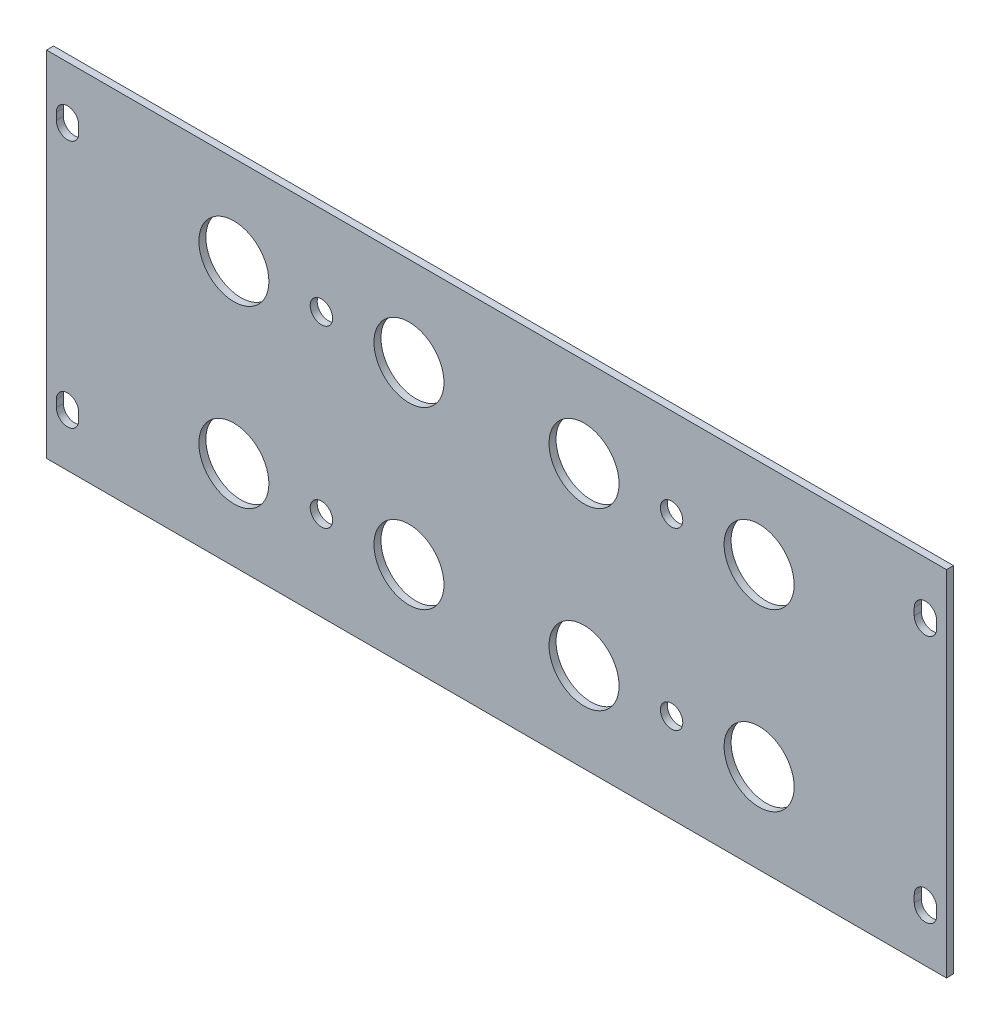
SolidWorks part; units mm, degrees
ref_plane "Plan de face" through (0, 0, 0) normal (0, 0, 1) x (1, 0, 0)
ref_plane "Plan de dessus" through (0, 0, 0) normal (0, 1, 0) x (1, 0, 0)
ref_plane "Plan de droite" through (0, 0, 0) normal (1, 0, 0) x (0, 0, -1)
sketch "Esquisse1" plane through (0, 0, 0) normal (0, 0, 1) x (1, 0, 0)
  line L0 (-64.25, 25.25) -> (-64.25, -25.25)
  line L1 (-64.25, 25.25) -> (-64.25, -25.25)
  line L2 (-64.25, -25.25) -> (64.25, -25.25)
  line L3 (-64.25, -25.25) -> (64.25, -25.25)
  line L4 (64.25, -25.25) -> (64.25, 25.25)
  line L5 (64.25, -25.25) -> (64.25, 25.25)
  line L6 (64.25, 25.25) -> (-64.25, 25.25)
  line L7 (64.25, 25.25) -> (-64.25, 25.25)
  line L8 (-59.65, 17.25) -> (-59.65, 18.25)
  line L9 (-59.65, 17.25) -> (-59.65, 18.25)
  line L10 (-62.85, 18.25) -> (-62.85, 17.25)
  line L11 (-62.85, 18.25) -> (-62.85, 17.25)
  line L12 (-59.65, -18.25) -> (-59.65, -17.25)
  line L13 (-59.65, -18.25) -> (-59.65, -17.25)
  line L14 (-62.85, -17.25) -> (-62.85, -18.25)
  line L15 (-62.85, -17.25) -> (-62.85, -18.25)
  line L16 (59.65, 18.25) -> (59.65, 17.25)
  line L17 (59.65, 18.25) -> (59.65, 17.25)
  line L18 (62.85, 17.25) -> (62.85, 18.25)
  line L19 (62.85, 17.25) -> (62.85, 18.25)
  line L20 (62.85, -18.25) -> (62.85, -17.25)
  line L21 (62.85, -18.25) -> (62.85, -17.25)
  line L22 (59.65, -17.25) -> (59.65, -18.25)
  line L23 (59.65, -17.25) -> (59.65, -18.25)
  line L24 (-64.25, 25.25) -> (-64.25, -25.25)
  line L25 (-64.25, -25.25) -> (64.25, -25.25)
  line L26 (64.25, -25.25) -> (64.25, 25.25)
  line L27 (64.25, 25.25) -> (-64.25, 25.25)
  line L28 (-59.65, 17.25) -> (-59.65, 18.25)
  line L29 (-62.85, 18.25) -> (-62.85, 17.25)
  line L30 (-59.65, -18.25) -> (-59.65, -17.25)
  line L31 (-62.85, -17.25) -> (-62.85, -18.25)
  line L32 (59.65, 18.25) -> (59.65, 17.25)
  line L33 (62.85, 17.25) -> (62.85, 18.25)
  line L34 (62.85, -18.25) -> (62.85, -17.25)
  line L35 (59.65, -17.25) -> (59.65, -18.25)
  line L36 (-64.25, 25.25) -> (-64.25, -25.25)
  line L37 (-64.25, -25.25) -> (64.25, -25.25)
  line L38 (64.25, -25.25) -> (64.25, 25.25)
  line L39 (64.25, 25.25) -> (-64.25, 25.25)
  line L40 (-59.65, 17.25) -> (-59.65, 18.25)
  line L41 (-62.85, 18.25) -> (-62.85, 17.25)
  line L42 (-59.65, -18.25) -> (-59.65, -17.25)
  line L43 (-62.85, -17.25) -> (-62.85, -18.25)
  line L44 (59.65, 18.25) -> (59.65, 17.25)
  line L45 (62.85, 17.25) -> (62.85, 18.25)
  line L46 (62.85, -18.25) -> (62.85, -17.25)
  line L47 (59.65, -17.25) -> (59.65, -18.25)
  circle A0 centre (-37.5, 12.5) radius 5
  circle A1 centre (-37.5, 12.5) radius 5
  circle A2 centre (-12.5, 12.5) radius 5
  circle A3 centre (-12.5, 12.5) radius 5
  circle A4 centre (12.5, 12.5) radius 5
  circle A5 centre (12.5, 12.5) radius 5
  circle A6 centre (37.5, 12.5) radius 5
  circle A7 centre (37.5, 12.5) radius 5
  circle A8 centre (37.5, -12.5) radius 5
  circle A9 centre (37.5, -12.5) radius 5
  circle A10 centre (-12.5, -12.5) radius 5
  circle A11 centre (-12.5, -12.5) radius 5
  circle A12 centre (-37.5, -12.5) radius 5
  circle A13 centre (-37.5, -12.5) radius 5
  circle A14 centre (12.5, -12.5) radius 5
  circle A15 centre (12.5, -12.5) radius 5
  arc A16 (-62.85, 17.25) -> (-59.65, 17.25) centre (-61.25, 17.25) ccw
  arc A17 (-62.85, 17.25) -> (-59.65, 17.25) centre (-61.25, 17.25) ccw
  arc A18 (-59.65, 18.25) -> (-62.85, 18.25) centre (-61.25, 18.25) ccw
  arc A19 (-59.65, 18.25) -> (-62.85, 18.25) centre (-61.25, 18.25) ccw
  arc A20 (-62.85, -18.25) -> (-59.65, -18.25) centre (-61.25, -18.25) ccw
  arc A21 (-62.85, -18.25) -> (-59.65, -18.25) centre (-61.25, -18.25) ccw
  arc A22 (-59.65, -17.25) -> (-62.85, -17.25) centre (-61.25, -17.25) ccw
  arc A23 (-59.65, -17.25) -> (-62.85, -17.25) centre (-61.25, -17.25) ccw
  arc A24 (62.85, 18.25) -> (59.65, 18.25) centre (61.25, 18.25) ccw
  arc A25 (62.85, 18.25) -> (59.65, 18.25) centre (61.25, 18.25) ccw
  arc A26 (59.65, 17.25) -> (62.85, 17.25) centre (61.25, 17.25) ccw
  arc A27 (59.65, 17.25) -> (62.85, 17.25) centre (61.25, 17.25) ccw
  arc A28 (59.65, -18.25) -> (62.85, -18.25) centre (61.25, -18.25) ccw
  arc A29 (59.65, -18.25) -> (62.85, -18.25) centre (61.25, -18.25) ccw
  arc A30 (62.85, -17.25) -> (59.65, -17.25) centre (61.25, -17.25) ccw
  arc A31 (62.85, -17.25) -> (59.65, -17.25) centre (61.25, -17.25) ccw
  circle A32 centre (25, -12.5) radius 1.6
  circle A33 centre (25, -12.5) radius 1.6
  circle A34 centre (-25, -12.5) radius 1.6
  circle A35 centre (-25, -12.5) radius 1.6
  circle A36 centre (-25, 12.5) radius 1.6
  circle A37 centre (-25, 12.5) radius 1.6
  circle A38 centre (25, 12.5) radius 1.6
  circle A39 centre (25, 12.5) radius 1.6
  circle A40 centre (-37.5, 12.5) radius 5
  circle A41 centre (-12.5, 12.5) radius 5
  circle A42 centre (12.5, 12.5) radius 5
  circle A43 centre (37.5, 12.5) radius 5
  circle A44 centre (37.5, -12.5) radius 5
  circle A45 centre (-12.5, -12.5) radius 5
  circle A46 centre (-37.5, -12.5) radius 5
  circle A47 centre (12.5, -12.5) radius 5
  arc A48 (-62.85, 17.25) -> (-59.65, 17.25) centre (-61.25, 17.25) ccw
  arc A49 (-59.65, 18.25) -> (-62.85, 18.25) centre (-61.25, 18.25) ccw
  arc A50 (-62.85, -18.25) -> (-59.65, -18.25) centre (-61.25, -18.25) ccw
  arc A51 (-59.65, -17.25) -> (-62.85, -17.25) centre (-61.25, -17.25) ccw
  arc A52 (62.85, 18.25) -> (59.65, 18.25) centre (61.25, 18.25) ccw
  arc A53 (59.65, 17.25) -> (62.85, 17.25) centre (61.25, 17.25) ccw
  arc A54 (59.65, -18.25) -> (62.85, -18.25) centre (61.25, -18.25) ccw
  arc A55 (62.85, -17.25) -> (59.65, -17.25) centre (61.25, -17.25) ccw
  circle A56 centre (25, -12.5) radius 1.6
  circle A57 centre (-25, -12.5) radius 1.6
  circle A58 centre (-25, 12.5) radius 1.6
  circle A59 centre (25, 12.5) radius 1.6
  circle A60 centre (-37.5, 12.5) radius 5
  circle A61 centre (-12.5, 12.5) radius 5
  circle A62 centre (12.5, 12.5) radius 5
  circle A63 centre (37.5, 12.5) radius 5
  circle A64 centre (37.5, -12.5) radius 5
  circle A65 centre (-12.5, -12.5) radius 5
  circle A66 centre (-37.5, -12.5) radius 5
  circle A67 centre (12.5, -12.5) radius 5
  arc A68 (-62.85, 17.25) -> (-59.65, 17.25) centre (-61.25, 17.25) ccw
  arc A69 (-59.65, 18.25) -> (-62.85, 18.25) centre (-61.25, 18.25) ccw
  arc A70 (-62.85, -18.25) -> (-59.65, -18.25) centre (-61.25, -18.25) ccw
  arc A71 (-59.65, -17.25) -> (-62.85, -17.25) centre (-61.25, -17.25) ccw
  arc A72 (62.85, 18.25) -> (59.65, 18.25) centre (61.25, 18.25) ccw
  arc A73 (59.65, 17.25) -> (62.85, 17.25) centre (61.25, 17.25) ccw
  arc A74 (59.65, -18.25) -> (62.85, -18.25) centre (61.25, -18.25) ccw
  arc A75 (62.85, -17.25) -> (59.65, -17.25) centre (61.25, -17.25) ccw
  circle A76 centre (25, -12.5) radius 1.6
  circle A77 centre (-25, -12.5) radius 1.6
  circle A78 centre (-25, 12.5) radius 1.6
  circle A79 centre (25, 12.5) radius 1.6
extrude "Boss.-Extru.1" add sketch "Esquisse1" along normal blind 1 contours L4 L6 L0 L2 A38 A36 A34 A32 A30 L20 A28 L22 A26 L16 A24 L18 A22 L12 A20 L14 A18 L8 A16 L10 A14 A12 A10 A8 A6 A4 A2 A0
